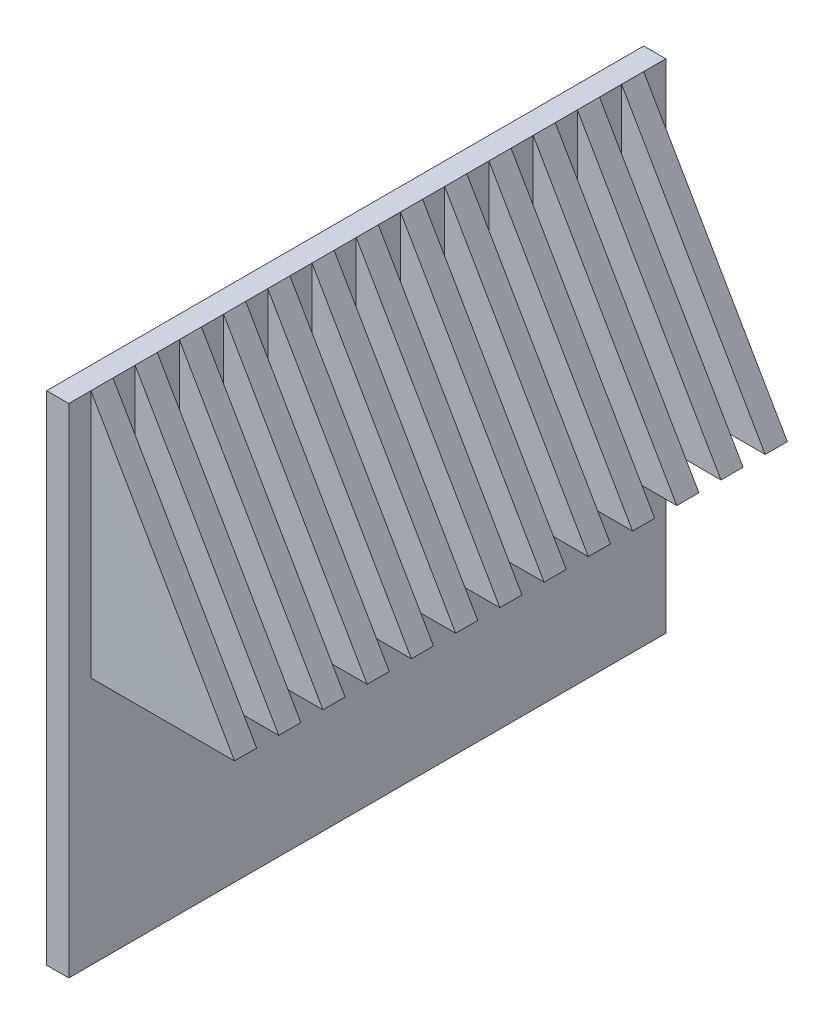
SolidWorks part; units mm, degrees
material "A286 Iron Base Superalloy"
ref_plane "Front Plane" through (0, 0, 0) normal (0, 0, 1) x (1, 0, 0)
ref_plane "Top Plane" through (0, 0, 0) normal (0, 1, 0) x (1, 0, 0)
ref_plane "Right Plane" through (0, 0, 0) normal (1, 0, 0) x (0, 0, -1)
sketch "Sketch2" plane through (0, 0, 0) normal (1, 0, 0) x (0, 0, -1)
  line L1 (0, 0) -> (270, 0)
  line L2 (0, 0) -> (0, 225)
  line L3 (0, 225) -> (270, 225)
  line L4 (270, 0) -> (270, 225)
  dimension "D1" = 270
  dimension "D2" = 225
extrude "Boss-Extrude1" add sketch "Sketch2" along normal blind 10
sketch "Sketch4" plane through (0, 0, 0) normal (0, 0, 1) x (1, 0, 0)
  line L0 (10, 225) -> (74.9519, 112.5)
  line L1 (10, 225) -> (10, 0) construction
  line L2 (10, 225) -> (10, 112.5)
  line L3 (10, 112.5) -> (74.9519, 112.5)
  dimension "D1" = 30
  dimension "D2" = 112.5
extrude "Boss-Extrude4" add sketch "Sketch4" against normal up to vertex (270 mm away) up to point (10, 225, -270)
sketch "Sketch5" plane through (0, 112.5, 0) normal (0, -1, 0) x (1, 0, 0)
  line L0 (10, -270) -> (10, -260)
  line L1 (10, -270) -> (10, 0) construction
  line L2 (10, -260) -> (74.9519, -260)
  line L3 (74.9519, -270) -> (74.9519, 0) construction
  line L8 (10, -260) -> (74.9519, -260)
  line L9 (10, -260) -> (10, -270)
  line L10 (10, -270) -> (74.9519, -270)
  line L11 (74.9519, -260) -> (74.9519, -270)
  line M3 (10, 0) -> (10, -270)
  line M4 (10, -270) -> (74.9519, -270)
  line M5 (74.9519, -270) -> (74.9519, 0)
  dimension "D1" = 10
extrude "Cut-Extrude1" cut sketch "Sketch5" against normal through all contours L2 M3 M4 M5
sketch "Sketch6" plane through (0, 112.5, 0) normal (0, -1, 0) x (1, 0, 0)
  line L0 (10, -260) -> (10, -250)
  line L1 (10, 0) -> (10, -270) construction
  line L2 (10, -250) -> (74.9519, -250)
  line L3 (74.9519, -260) -> (74.9519, 0) construction
  line L4 (0, -260) -> (0, -240)
  line L5 (10, -250) -> (10, -240)
  line L6 (0, -240) -> (74.9519, -240) construction
  line L7 (10, -260) -> (10, 0) construction
  line L8 (10, -240) -> (10, -230)
  line L9 (10, -230) -> (10, -220)
  line L10 (10, -220) -> (10, -210)
  line L11 (10, -210) -> (10, -200)
  line L12 (10, -200) -> (10, -190)
  line L13 (10, -190) -> (10, -130)
  line L14 (10, -130) -> (10, -111.3523)
  line L15 (10, -111.3523) -> (10, -94.5422)
  line L16 (10, -94.5422) -> (10, -79.4415)
  line L17 (10, -79.4415) -> (10, -62.0615)
  line L18 (10, -62.0615) -> (10, -44.9664)
  line L19 (10, -44.9664) -> (10, -28.1562)
  line L20 (10, -28.1562) -> (10, -14.4802)
  line L21 (10, -14.4802) -> (10, 0)
  line L22 (10, -240) -> (74.9519, -240)
  line L23 (74.9519, -240) -> (74.9519, -250)
  line L24 (10, -240) -> (10, -250)
  line M18 (10, 0) -> (10, -260)
  line M20 (74.9519, -260) -> (74.9519, 0)
  dimension "D1" = 10
  dimension "D3" = 10
  dimension "D4" = 10
  dimension "D5" = 10
  dimension "D6" = 10
  dimension "D7" = 10
  dimension "D8" = 10
  dimension "D2" = 10
extrude "Cut-Extrude2" cut sketch "Sketch6" against normal through all contours L22 L2 M18 M20
sketch "Sketch7" plane through (0, 112.5, 0) normal (0, -1, 0) x (1, 0, 0)
  line L0 (10, 0) -> (10, -10)
  line L1 (10, 0) -> (10, -270) construction
  line L2 (10, -10) -> (74.9519, -10)
  line L3 (74.9519, -240) -> (74.9519, 0) construction
  line L4 (10, -20) -> (74.9519, -20)
  line L5 (10, -30) -> (74.9519, -30)
  line L6 (10, -40) -> (74.9519, -40)
  line L7 (10, -50) -> (74.9519, -50)
  line L8 (10, -60) -> (74.9519, -60)
  line L9 (10, -70) -> (74.9519, -70)
  line L10 (10, -80) -> (74.9519, -80)
  line L11 (10, -90) -> (74.9519, -90)
  line L12 (10, -100) -> (74.9519, -100)
  line L13 (10, -110) -> (74.9519, -110)
  line L14 (10, -120) -> (74.9519, -120)
  line L15 (10, -130) -> (74.9519, -130)
  line L16 (10, -140) -> (74.9519, -140)
  line L17 (10, -150) -> (74.9519, -150)
  line L18 (10, -160) -> (74.9519, -160)
  line L19 (10, -170) -> (74.9519, -170)
  line L20 (10, -180) -> (74.9519, -180)
  line L21 (10, -190) -> (74.9519, -190)
  line L22 (10, -200) -> (74.9519, -200)
  line L23 (10, -210) -> (74.9519, -210)
  line L24 (10, -220) -> (74.9519, -220)
  line L25 (10, -230) -> (74.9519, -230)
  line L26 (10, -240) -> (10, 0) construction
  line L27 (74.9519, -10) -> (74.9519, -20)
  line L28 (10, -10) -> (10, -240)
  line M25 (10, 0) -> (10, -240)
  line M27 (74.9519, -240) -> (74.9519, 0)
  line M28 (74.9519, 0) -> (10, 0)
  dimension "D1" = 10
  dimension "D2" = 23
extrude "Cut-Extrude3" cut sketch "Sketch7" against normal through all contours L2 M25 M27 M28 | L5 L4 M25 M27 | L7 L6 M25 M27 | L9 L8 M25 M27 | L11 L10 M25 M27 | L13 L12 M25 M27 | L15 L14 M25 M27 | L17 L16 M25 M27 | L19 L18 M25 M27 | L21 L20 M25 M27 | L23 L22 M25 M27 | L25 L24 M25 M27
